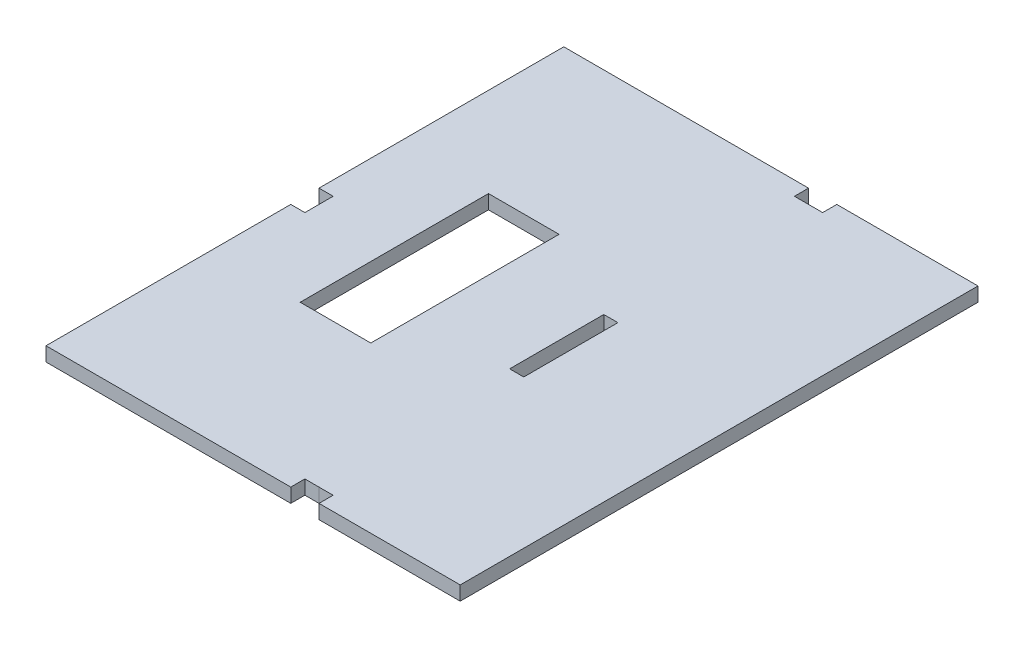
SolidWorks part; units mm, degrees
ref_plane "Спереди" through (0, 0, 0) normal (0, 0, 1) x (1, 0, 0)
ref_plane "Сверху" through (0, 0, 0) normal (0, 1, 0) x (1, 0, 0)
ref_plane "Справа" through (0, 0, 0) normal (1, 0, 0) x (0, 0, -1)
other "Configuration Table"
sketch "Эскиз4" plane through (0, 0, 0) normal (0, 1, 0) x (1, 0, 0)
  line L0 (88, 110) -> (88, 0)
  line L1 (0, 0) -> (52, 0)
  line L2 (0, 0) -> (0, 52)
  line L3 (0, 110) -> (52, 110)
  line L5 (58, 0) -> (88, 0)
  line L6 (55, 107) -> (52, 107)
  line L7 (52, 107) -> (55, 107)
  line L8 (55, 107) -> (58, 107)
  line L9 (52, 107) -> (52, 110)
  line L10 (58, 107) -> (58, 110)
  line L11 (58, 3) -> (58, 0)
  line L12 (55, 2.9916) -> (58, 3)
  line L13 (55, 2.9916) -> (52, 3)
  line L14 (52, 3) -> (52, 0)
  line L15 (3, 55) -> (3, 58)
  line L16 (3, 55) -> (3, 52)
  line L17 (3, 58) -> (0, 58)
  line L18 (3, 52) -> (0, 52)
  line L19 (55, 107) -> (55, 2.9916) construction
  line L20 (3, 55) -> (55, 54.9958) construction
  line L22 (0, 58) -> (0, 110)
  line L23 (58, 110) -> (88, 110)
  point P1 (58, 108.5)
  dimension "D1" = 55
  dimension "D2" = 110
  dimension "D3" = 3
  dimension "D4" = 3
  dimension "D5" = 6
  dimension "D6" = 3
  dimension "D7" = 3
  dimension "D8" = 3
  dimension "D9" = 3
  dimension "D10" = 3
  dimension "D11" = 3
  dimension "D12" = 3
  dimension "D13" = 30
extrude "Бобышка-Вытянуть3" add sketch "Эскиз4" along normal blind 3
sketch "Sketch1" plane through (0, 3, 0) normal (0, 1, 0) x (1, 0, 0)
  line L0 (3, 52) -> (3, 58) construction
  line L13 (3, 55) -> (107, 55) construction
  line L15 (55, 107) -> (55, 3) construction
  line L16 (52, 107) -> (58, 107) construction
  line L19 (19, 75) -> (34, 75)
  line L20 (19, 75) -> (19, 35)
  line L21 (19, 35) -> (34, 35)
  line L22 (34, 75) -> (34, 35)
  line L23 (53.5, 65) -> (56.5, 65)
  line L24 (53.5, 65) -> (53.5, 45)
  line L25 (53.5, 45) -> (56.5, 45)
  line L26 (56.5, 65) -> (56.5, 45)
  point P8 (0, 0)
  point P9 (0, 0)
  dimension "D1" = 3
  dimension "D2" = 20
  dimension "D3" = 16
  dimension "D4" = 15
  dimension "D5" = 40
extrude "Cut-Extrude1" cut sketch "Sketch1" against normal blind 10
